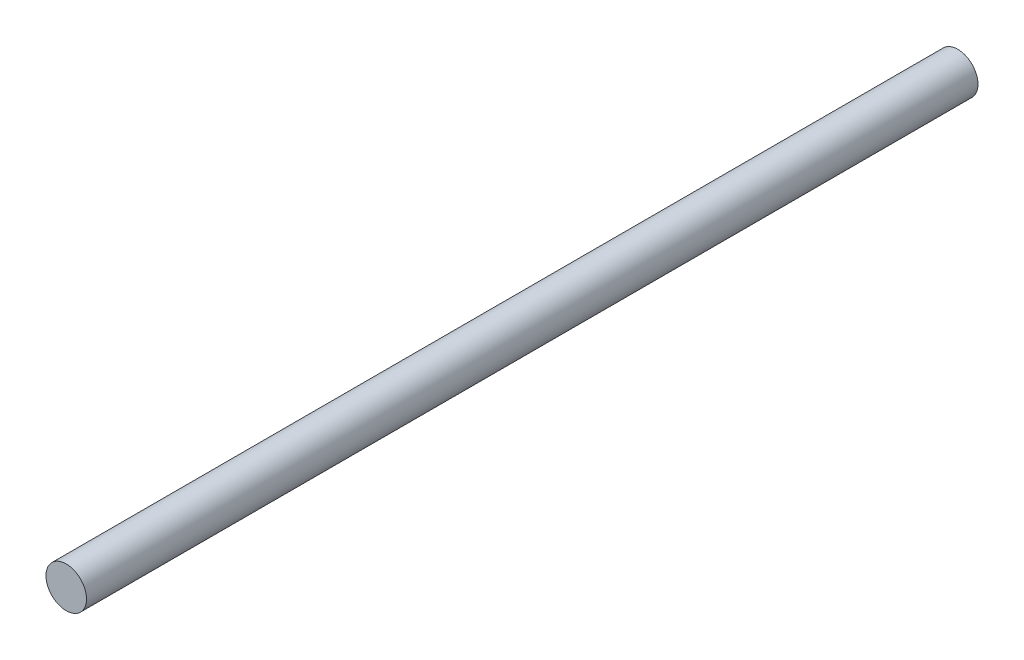
SolidWorks part; units mm, degrees
ref_plane "Front Plane" through (0, 0, 0) normal (0, 0, 1) x (1, 0, 0)
ref_plane "Top Plane" through (0, 0, 0) normal (0, 1, 0) x (1, 0, 0)
ref_plane "Right Plane" through (0, 0, 0) normal (1, 0, 0) x (0, 0, -1)
sketch "Sketch1" plane through (0, 0, 0) normal (0, 0, 1) x (1, 0, 0)
  circle A0 centre (0, 0) radius 3.175
  dimension "D1" = 6.35
extrude "Boss-Extrude1" add sketch "Sketch1" along normal blind 139.7
